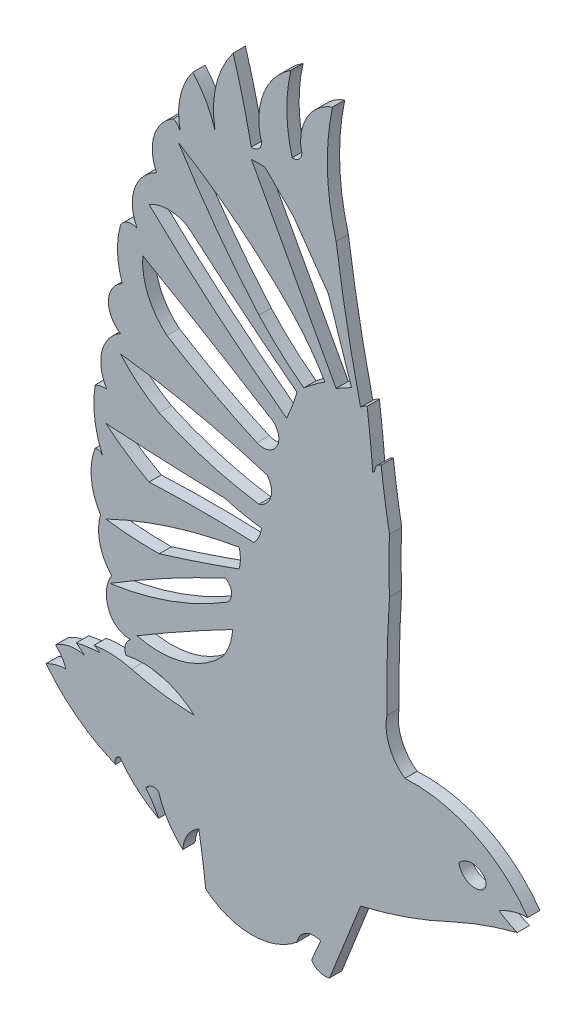
SolidWorks part; units mm, degrees
ref_plane "정면" through (0, 0, 0) normal (0, 0, 1) x (1, 0, 0)
ref_plane "윗면" through (0, 0, 0) normal (0, 1, 0) x (1, 0, 0)
ref_plane "우측면" through (0, 0, 0) normal (1, 0, 0) x (0, 0, -1)
sketch "스케치1" plane through (0, 0, 0) normal (0, 0, 1) x (1, 0, 0)
  line L0 (-3.4876, 17.4021) -> (0.6622, 9.7585)
  line L1 (0.6622, 9.7585) -> (1.4171, 10.1684)
  line L2 (1.4171, 10.1684) -> (0.2842, 13.5803)
  line L3 (0.2842, 13.5803) -> (-1.4127, 15.9936)
  line L4 (-1.4127, 15.9936) -> (-2.8212, 17.4021)
  line L5 (-2.8212, 17.4021) -> (-3.4876, 17.4021)
  arc A0 (4.0303, -5.0904) -> (10.0432, -7.9841) centre (4.4325, -11.9488) cw
  arc A1 (8.6406, -8.3987) -> (10.0432, -7.9841) centre (10.1324, -10.8659) cw
  arc A2 (-21.5528, -11.8456) -> (-18.1597, -10.6986) centre (-9.3745, -42.2777) cw construction
  arc A3 (-18.1597, -10.6986) -> (-14.6272, -10.1644) centre (-6.3724, -76.6992) cw construction
  arc A4 (8.6406, -8.3987) -> (9.5332, -8.8774) centre (11.0227, -5.0285) ccw
  arc A5 (9.5332, -8.8774) -> (6.3411, -10.017) centre (14.442, -27.6692) ccw
  arc A6 (6.3411, -10.017) -> (1.86, -11.5874) centre (-3.2136, 10.0672) cw
  arc A7 (1.86, -11.5874) -> (0.3438, -15.3979) centre (-2251.6453, 882.9083) cw
  arc A8 (0.3438, -15.3979) -> (-0.5375, -15.0856) centre (0.1127, -14.6502) cw
  arc A9 (-0.5375, -15.0856) -> (-0.0883, -14.0477) centre (14.2269, -20.8601) cw
  arc A10 (-0.0883, -14.0477) -> (-1.2554, -14.682) centre (-0.4124, -14.8423) ccw
  arc A11 (-1.2554, -14.682) -> (-5.722, -14.6502) centre (-3.4698, -11.9989) cw
  arc A12 (-5.722, -14.6502) -> (-6.0562, -12.2734) centre (-51.0323, -19.8091) ccw
  arc A13 (-6.0562, -12.2734) -> (-6.84, -13.5462) centre (-5.2781, -13.6302) ccw
  arc A14 (-6.84, -13.5462) -> (-8.0296, -11.673) centre (-4.1301, -10.511) cw
  arc A15 (-8.0296, -11.673) -> (-8.6479, -11.8456) centre (-8.2561, -12.0553) ccw
  arc A16 (-8.6479, -11.8456) -> (-8.0296, -12.8177) centre (-11.6015, -14.4071) cw
  arc A17 (-8.0296, -12.8177) -> (-9.9312, -11.1632) centre (-5.3996, -7.8747) cw
  arc A18 (-9.9312, -11.1632) -> (-10.1401, -11.5874) centre (-9.843, -11.4702) ccw
  arc A19 (-10.1401, -11.5874) -> (-10.281, -11.5233) centre (-6.3907, -3.1665) cw
  arc A20 (0.6622, 15.9936) -> (1.86, 9.559) centre (73.887, 26.2956) ccw
  arc A21 (2.4571, 7.1079) -> (2.553, 7.2121) centre (2.3689, 7.2853) ccw
  arc A22 (-12.7277, -8.3987) -> (-13.0734, -7.9838) centre (-14.6523, -9.6508) ccw
  arc A23 (-13.0734, -7.9838) -> (-11.6405, -7.7212) centre (-12.0772, -9.3791) cw
  arc A24 (-11.6405, -7.7212) -> (-12.0493, -7.3822) centre (-9.1409, -4.2905) cw
  arc A25 (-12.0493, -7.3822) -> (-10.9168, -7.225) centre (-10.3638, -15.3659) cw
  arc A26 (-10.9168, -7.225) -> (-11.1862, -7.0551) centre (-11.4425, -7.7602) ccw
  arc A27 (-11.1862, -7.0551) -> (-9.3519, -7.1502) centre (-10.4866, -11.3) cw
  arc A28 (-9.3519, -7.1502) -> (-6.2931, -7.5709) centre (-5.977, 6.0567) ccw
  arc A29 (-6.2931, -7.5709) -> (-9.6279, -6.702) centre (-8.7995, -10.3567) ccw
  arc A30 (-9.6279, -6.702) -> (-9.3907, -5.9192) centre (-9.0324, -6.4551) cw
  arc A31 (-9.3907, -5.9192) -> (-10.4173, -5.3037) centre (-9.4328, -4.8257) cw
  arc A32 (-10.4173, -5.3037) -> (-10.3246, -3.6754) centre (-8.9352, -4.5713) cw
  arc A33 (-10.3246, -3.6754) -> (-10.8688, -1.3734) centre (-8.5907, -2.0501) cw
  arc A34 (-10.8688, -1.3734) -> (-11.1353, 1.3204) centre (-8.3122, 0.2395) cw
  arc A35 (-11.1353, 1.3204) -> (-10.781, 1.2108) centre (-11.0238, 1.0532) cw
  arc A36 (-10.781, 1.2108) -> (-11.1353, 4.0063) centre (-6.1683, 3.2155) cw
  arc A37 (-11.1353, 4.0063) -> (-10.5633, 4.1153) centre (-10.6112, 2.8109) cw
  arc A38 (-10.5633, 4.1153) -> (-9.892, 6.8068) centre (-8.9431, 5.1406) cw
  arc A39 (-9.892, 6.8068) -> (-9.8037, 8.9673) centre (-9.2443, 7.8624) cw
  arc A40 (-9.8037, 8.9673) -> (-9.892, 11.4064) centre (-6.058, 10.324) cw
  arc A41 (-9.892, 11.4064) -> (-9.0807, 11.6764) centre (-9.343, 11.1104) cw
  arc A42 (-9.0807, 11.6764) -> (-8.1255, 14.5102) centre (-7.2392, 12.6336) cw
  arc A43 (-8.1255, 14.5102) -> (-7.3015, 17.2052) centre (-6.2807, 15.4197) cw
  arc A44 (-7.3015, 17.2052) -> (-6.9693, 16.8519) centre (-7.6212, 16.5719) cw
  arc A45 (-6.9693, 16.8519) -> (-6.3515, 19.657) centre (-3.6218, 17.5852) cw
  arc A46 (-6.3515, 19.657) -> (-5.2604, 17.7215) centre (-10.1734, 16.2273) cw
  arc A47 (-5.2604, 17.7215) -> (-4.3768, 21.4553) centre (-0.6095, 18.5923) cw
  arc A48 (-4.3768, 21.4553) -> (-3.4876, 17.9119) centre (-43.4662, 9.7625) cw
  arc A49 (-3.4876, 17.9119) -> (-3.0413, 18.5555) centre (-3.4262, 18.3459) ccw
  arc A50 (-3.0413, 18.5555) -> (-1.5506, 22.1347) centre (0.2842, 19.2705) cw
  arc A51 (-1.5506, 22.1347) -> (-1.4896, 18.4598) centre (5.7562, 20.4181) ccw
  arc A52 (-1.4896, 18.4598) -> (-1.058, 19.0732) centre (-1.4494, 18.8901) ccw
  arc A53 (-1.058, 19.0732) -> (0.4872, 21.601) centre (1.3115, 19.3609) cw
  arc A54 (0.4872, 21.601) -> (0.6622, 15.9936) centre (12.0768, 19.1562) ccw
  arc A55 (2.553, 7.2121) -> (2.8647, 7.611) centre (2.9778, 7.2013) cw
  arc A56 (1.86, 9.559) -> (2.1816, 9.7585) centre (2.4377, 8.9869) cw
  arc A57 (2.1816, 9.7585) -> (2.4571, 7.1079) centre (-50.3335, 2.9597) cw
  arc A58 (2.8647, 7.611) -> (3.2753, 4.883) centre (47.7794, 12.9774) ccw
  arc A59 (3.2753, 4.883) -> (3.2753, 2.2175) centre (31.1223, 3.5502) ccw
  arc A60 (3.2753, 2.2175) -> (3.1536, -2.8552) centre (67.387, -1.8593) ccw
  arc A61 (3.1536, -2.8552) -> (4.0303, -5.0904) centre (5.3151, -3.2969) ccw
  arc A62 (6.6777, -7.34) -> (7.9333, -7.34) centre (7.3055, -7.8524) cw
  arc A63 (6.6777, -7.34) -> (7.7081, -7.9838) centre (7.4572, -7.2388) ccw
  arc A64 (7.7081, -7.9838) -> (7.9333, -7.34) centre (7.5771, -7.5767) ccw
  arc A65 (-12.7277, -8.3987) -> (-21.43, -10.7497) centre (-6.5797, -48.4377) ccw construction
  arc A66 (-21.43, -10.7497) -> (-21.2918, -11.0896) centre (-22.0085, -11.183) cw construction
  arc A67 (-21.5528, -11.8456) -> (-21.3492, -12.4114) centre (-21.2084, -12.0412) ccw construction
  arc A68 (-21.43, -13.0202) -> (-21.3308, -13.937) centre (-20.2967, -13.3613) ccw construction
  arc A69 (-21.3308, -13.937) -> (-13.5731, -11.673) centre (39.267, -207.1537) cw construction
  arc A70 (-13.5731, -11.673) -> (-10.281, -11.5233) centre (-11.3284, -24.768) cw construction
  arc A71 (-4.4004, -2.9947) -> (-9.0807, -5.6) centre (36.8507, -82.6069) ccw
  arc A72 (-4.8596, -4.3536) -> (-9.0807, -5.6) centre (-8.0024, -1.481) cw
  arc A73 (-4.4004, -2.9947) -> (-4.8596, -4.3536) centre (-7.2018, -2.8051) cw
  arc A74 (-4.6727, -1.9718) -> (-10.4173, -4.0474) centre (-12.4757, 10.6372) cw
  arc A75 (-10.4173, -4.0474) -> (-4.7546, -0.9965) centre (19.2243, -52.284) cw
  arc A77 (-4.7546, -0.9965) -> (-4.6727, -1.9718) centre (-5.0389, -1.5115) cw
  arc A82 (-8.7995, 10.6544) -> (-7.6212, 7.8624) centre (-5.4898, 10.4066) ccw
  arc A83 (-8.7995, 10.6544) -> (-2.6035, 6.9309) centre (-104.8714, -156.2293) cw
  arc A84 (-2.6035, 6.9309) -> (-3.2136, 5.5186) centre (-2.9086, 6.2247) cw
  arc A85 (-3.2136, 5.5186) -> (-7.6212, 7.8624) centre (11.5472, 38.5931) cw
  arc A86 (-9.892, 5.946) -> (-2.7097, 4.396) centre (-14.967, -34.9865) cw
  arc A87 (-2.7097, 4.396) -> (-3.1119, 2.9597) centre (-3.3986, 3.8145) cw
  arc A88 (-3.1119, 2.9597) -> (-8.0024, 4.396) centre (-0.6391, 20.4232) cw
  arc A89 (-8.0024, 4.396) -> (-9.892, 5.946) centre (-4.3147, 10.8186) cw
  arc A90 (-10.6112, 2.6426) -> (-8.4967, 1.2108) centre (-2.8212, 11.8697) ccw
  arc A91 (-8.4967, 1.2108) -> (-3.3641, 1.2108) centre (-5.9304, -56.0103) cw
  arc A92 (-10.6112, 2.6426) -> (-4.7782, 2.3791) centre (-1.2505, 145.1711) ccw
  arc A93 (-4.7782, 2.3791) -> (-2.9892, 2.0073) centre (-1.8686, 11.8906) ccw
  arc A94 (-2.9892, 2.0073) -> (-3.3641, 1.2108) centre (-4.4004, 2.185) cw
  arc A95 (-10.6112, -1.415) -> (-4.0871, 0.6506) centre (0.0158, -23.644) cw
  arc A96 (-10.6112, -1.415) -> (-7.9984, -1.583) centre (-8.2169, 15.427) ccw
  arc A97 (-7.9984, -1.583) -> (-4.0871, -0.275) centre (-32.3457, 77.7235) ccw
  arc A98 (-4.0871, 0.6506) -> (-4.0871, -0.275) centre (-5.6845, 0.1878) cw
  arc A104 (-8.4967, 12.9774) -> (-1.7606, 7.2853) centre (40.0087, 63.5474) ccw
  arc A105 (-8.4967, 12.9774) -> (-6.5797, 12.9774) centre (-7.5382, 11.3555) cw
  arc A106 (-6.5797, 12.9774) -> (-1.2554, 8.64) centre (72.8552, 105.0491) ccw
  arc A107 (-1.2554, 8.64) -> (-1.7606, 7.2853) centre (-9.3741, 10.8958) cw
  arc A108 (-7.0477, 16.3189) -> (-3.1119, 10.9764) centre (27.4975, 37.6473) ccw
  arc A109 (-7.0477, 16.3189) -> (-1.4896, 11.8906) centre (-20.9377, -6.8172) cw
  arc A110 (-1.4896, 11.8906) -> (0.1127, 9.7585) centre (-9.5553, 4.1607) cw
  arc A111 (-3.1119, 10.9764) -> (-0.9209, 8.9869) centre (8.255, 21.2938) ccw
  arc A112 (-0.9209, 8.9869) -> (0.1127, 9.7585) centre (6.147, 0.5977) cw
  arc A122 (-12.7277, -8.3987) -> (-12.5708, -8.7461) centre (-13.7797, -9.0831) cw
  arc A123 (-21.2918, -11.0896) -> (-15.3413, -9.8258) centre (-16.0737, -21.0178) cw construction
  arc A124 (-21.3492, -12.4114) -> (-15.0671, -10.886) centre (-13.299, -31.8648) cw construction
  arc A125 (-21.43, -13.0202) -> (-14.9619, -11.2321) centre (-9.2805, -44.3769) cw construction
  arc A126 (-15.0671, -10.886) -> (-14.5716, -11.0896) centre (-15.2264, -11.9781) cw construction
  arc A127 (-14.9619, -11.2321) -> (-14.5716, -11.0896) centre (-16.1685, -7.3228) ccw construction
  arc A128 (-15.3413, -9.8258) -> (-14.6272, -10.1644) centre (-15.3178, -10.6986) cw construction
  arc A129 (-12.5708, -8.7461) -> (-13.5375, -9.01) centre (-12.4751, -10.9985) ccw
  arc A130 (-13.5375, -9.01) -> (-10.281, -11.5233) centre (-7.0477, -3.9674) ccw
extrude "보스-돌출1" add sketch "스케치1" along normal blind 0.6
